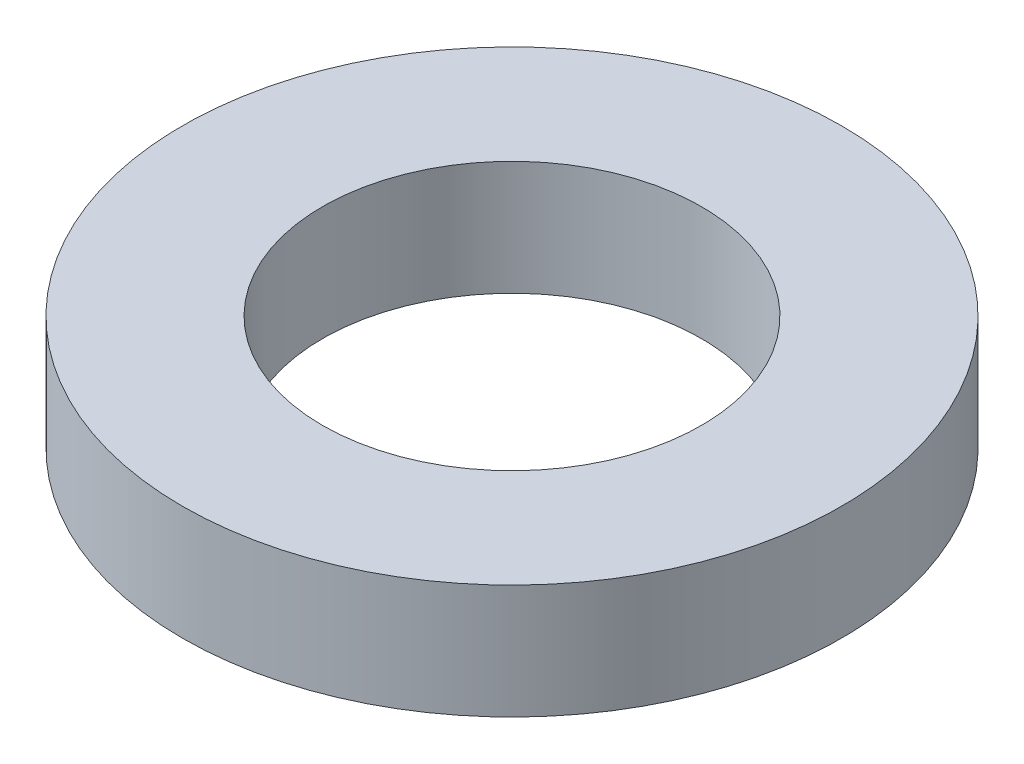
SolidWorks part; units mm, degrees
ref_plane "Front Plane" through (0, 0, 0) normal (0, 0, 1) x (1, 0, 0)
ref_plane "Top Plane" through (0, 0, 0) normal (0, 1, 0) x (1, 0, 0)
ref_plane "Right Plane" through (0, 0, 0) normal (1, 0, 0) x (0, 0, -1)
sketch "Sketch1" plane through (0, 0, 0) normal (0, 1, 0) x (1, 0, 0)
  circle A0 centre (0, 0) radius 16.5795
  circle A1 centre (0, 0) radius 28.833
extrude "Boss-Extrude1" add sketch "Sketch1" along normal blind 10
